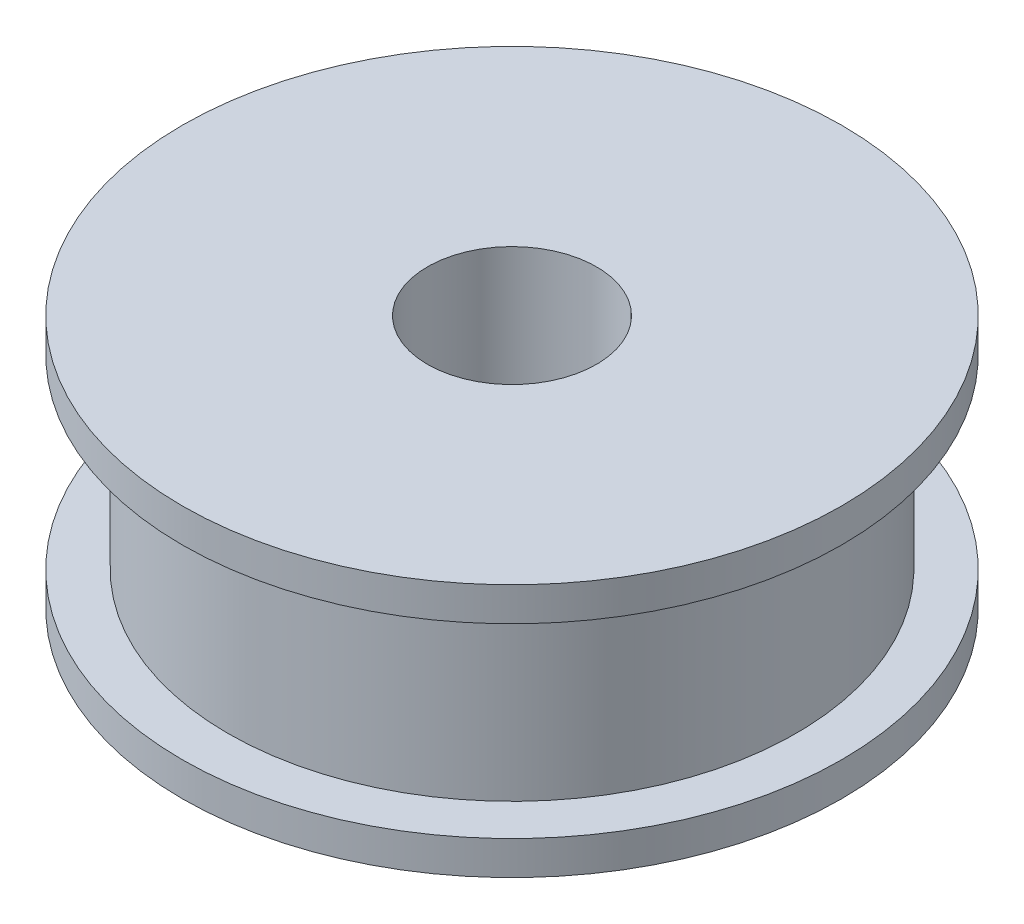
SolidWorks part; units mm, degrees
ref_plane "Front" through (0, 0, 0) normal (0, 0, 1) x (1, 0, 0)
ref_plane "Top" through (0, 0, 0) normal (0, 1, 0) x (1, 0, 0)
ref_plane "Right" through (0, 0, 0) normal (1, 0, 0) x (0, 0, -1)
sketch "草图1" plane through (0, 0, 0) normal (0, 0, 1) x (1, 0, 0)
  line L0 (0, 0) -> (19.5, 0)
  line L1 (0, 23.5758) -> (0, -15.2121) construction
  line L2 (19.5, 0) -> (19.5, -2)
  line L3 (19.5, -2) -> (16.805, -2)
  line L4 (16.805, -2) -> (16.805, -13)
  line L5 (16.805, -13) -> (19.5, -13)
  line L6 (19.5, -13) -> (19.5, -15)
  line L7 (19.5, -15) -> (0, -15)
  line L8 (0, 0) -> (0, -15)
  dimension "D1" = 2
  dimension "D2" = 2
  dimension "D3" = 11
  dimension "D4" = 19.5
  dimension "D5" = 33.61
  dimension "D6" = 19.5
revolve "旋转1" add sketch "草图1" angle 360 about L1
sketch "草图2" plane through (0, 0, 0) normal (0, 1, 0) x (1, 0, 0)
  circle A0 centre (0, 0) radius 5
  dimension "D1" = 10
extrude "切除-拉伸1" cut sketch "草图2" against normal through all
